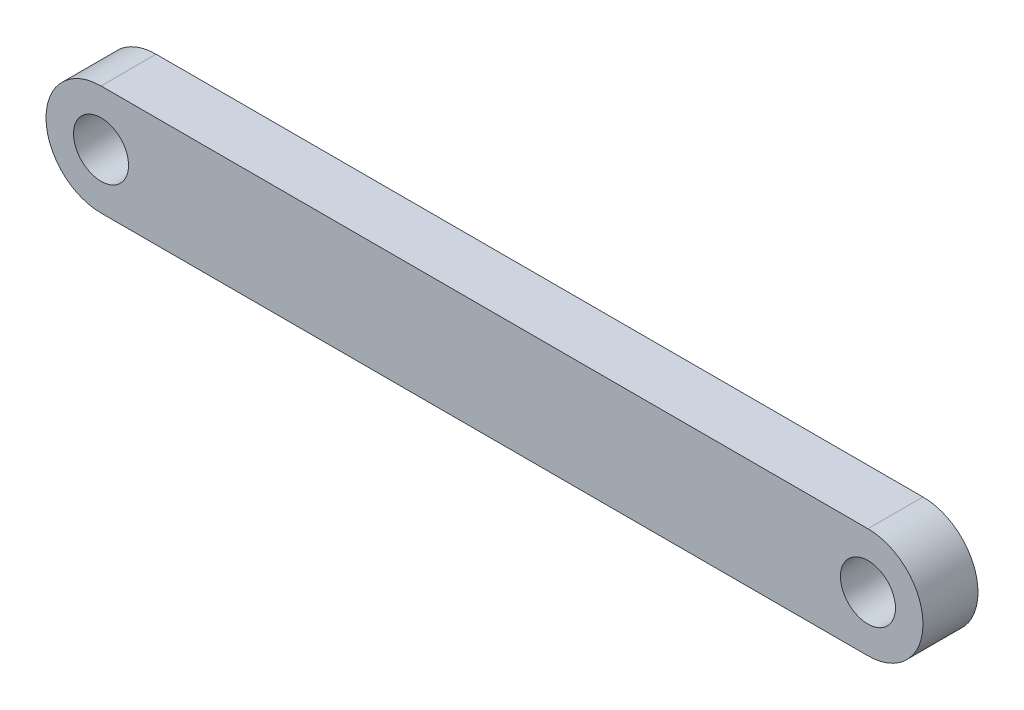
SolidWorks part; units mm, degrees
ref_plane "Plano frontal" through (0, 0, 0) normal (0, 0, 1) x (1, 0, 0)
ref_plane "Plano superior" through (0, 0, 0) normal (0, 1, 0) x (1, 0, 0)
ref_plane "Plano direito" through (0, 0, 0) normal (1, 0, 0) x (0, 0, -1)
sketch "Esboço1" plane through (0, 0, 0) normal (0, 0, 1) x (1, 0, 0)
  line L0 (-34.84, 5) -> (34.84, 5)
  line L1 (-37.895, 0) -> (37.895, 0) construction
  line L2 (-34.84, -5) -> (34.84, -5)
  arc A0 (-34.84, 5) -> (-34.84, -5) centre (-34.84, 0) ccw
  arc A1 (34.84, 5) -> (34.84, -5) centre (34.84, 0) cw
  circle A4 centre (-34.84, 0) radius 2.5
  circle A5 centre (34.84, 0) radius 2.5
  point P3 (0, 5)
  dimension "D1" = 69.68
  dimension "D2" = 5
extrude "Ressalto-extrusão1" add sketch "Esboço1" along normal blind 5
